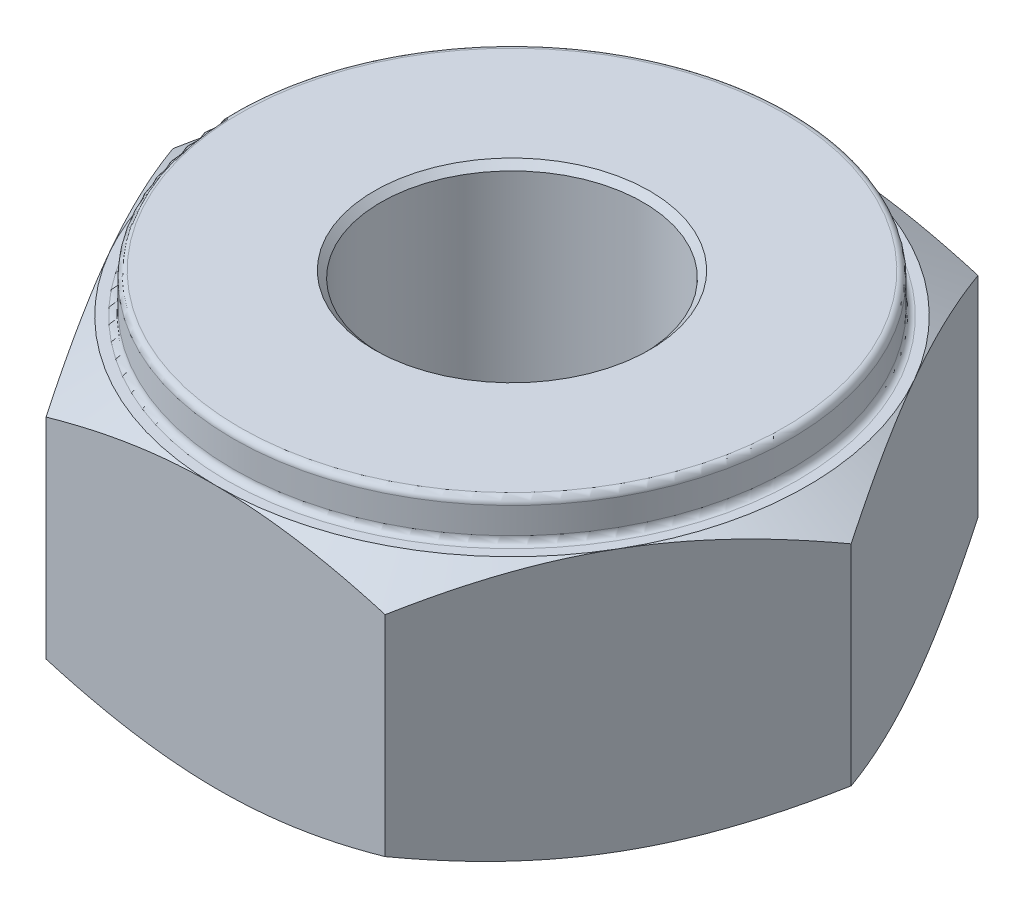
SolidWorks part; units mm, degrees
ref_plane "Front Plane" through (0, 0, 0) normal (0, 0, 1) x (1, 0, 0)
ref_plane "Top Plane" through (0, 0, 0) normal (0, 1, 0) x (1, 0, 0)
ref_plane "Right Plane" through (0, 0, 0) normal (1, 0, 0) x (0, 0, -1)
sketch "Sketch1" plane through (0, 0, 0) normal (0, 1, 0) x (1, 0, 0)
  line L1 (1.3093, 2.244) -> (-1.2888, 2.2559)
  line L2 (-1.2888, 2.2559) -> (-2.598, 0.0119)
  line L3 (-2.598, 0.0119) -> (-1.3093, -2.244)
  line L4 (-1.3093, -2.244) -> (1.2888, -2.2559)
  line L5 (1.2888, -2.2559) -> (2.598, -0.0119)
  line L6 (2.598, -0.0119) -> (1.3093, 2.244)
  circle A0 centre (0, 0) radius 1
  circle A1 centre (0, 0) radius 2.25 construction
  dimension "D1" = 2
  dimension "D2" = 4.5
extrude "Boss-Extrude1" add sketch "Sketch1" along normal blind 2
sketch "Sketch2" plane through (0, 2, 0) normal (0, 1, 0) x (1, 0, 0)
  circle A0 centre (0, 0) radius 2.25 construction
  circle A1 centre (0, 0) radius 2.25
extrude "Cut-Extrude2" cut sketch "Sketch2" against normal blind 1 draft 60 flip side to cut
sketch "Sketch3" plane through (0, 0, 0) normal (0, -1, 0) x (1, 0, 0)
  circle A0 centre (0, 0) radius 2.25 construction
  circle A1 centre (0, 0) radius 2.25
extrude "Cut-Extrude3" cut sketch "Sketch3" against normal blind 1 draft 60 flip side to cut
sketch "Sketch4" plane through (0, 2, 0) normal (0, 1, 0) x (1, 0, 0)
  circle A0 centre (0, 0) radius 2.125
  circle A1 centre (0, 0) radius 1 construction
  circle A2 centre (0, 0) radius 1
  dimension "D1" = 4.25
extrude "Boss-Extrude2" add sketch "Sketch4" along normal blind 0.3
fillet "Fillet1" radius 0.05 2 edges at (0, 2, 2.125) (0, 2.3, 2.125)
chamfer "Chamfer1" distance 0.05 angle 45 2 edges at (0, 0, 1) (0, 2.3, 1)
